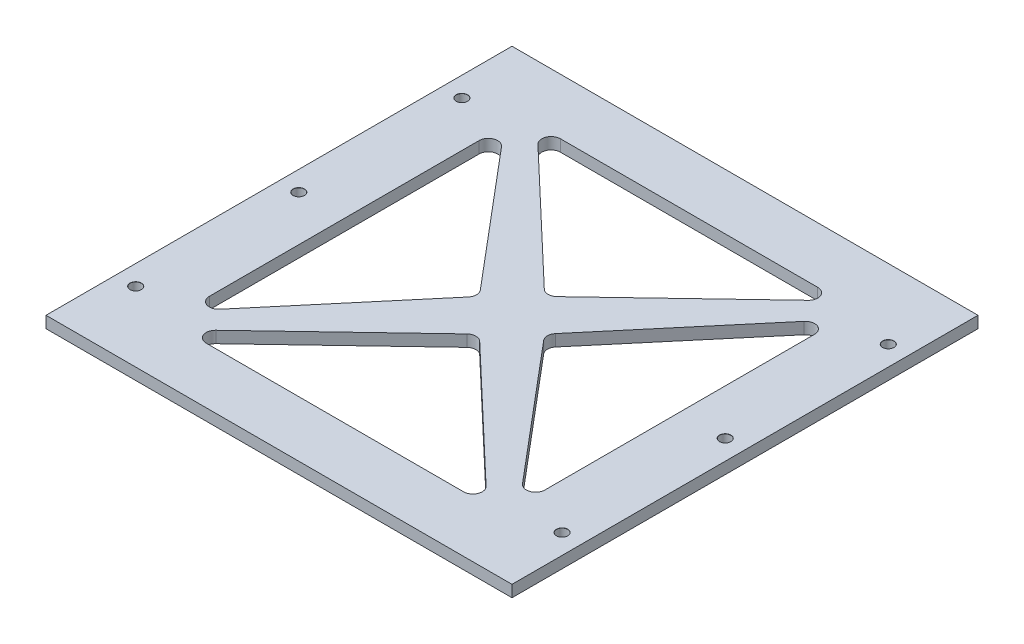
SolidWorks part; units mm, degrees
material "6061-T6 (SS)"
ref_plane "Front Plane" through (0, 0, 0) normal (0, 0, 1) x (1, 0, 0)
ref_plane "Top Plane" through (0, 0, 0) normal (0, 1, 0) x (1, 0, 0)
ref_plane "Right Plane" through (0, 0, 0) normal (1, 0, 0) x (0, 0, -1)
sketch "Sketch2" plane through (0, 0, 0) normal (0, 1, 0) x (1, 0, 0)
  line L1 (-50, -50) -> (50, -50)
  line L2 (-50, -50) -> (-50, 50)
  line L3 (-50, 50) -> (50, 50)
  line L4 (50, -50) -> (50, 50)
  line L5 (-50, -50) -> (50, 50) construction
  line L6 (-50, 50) -> (50, -50) construction
  point P0 (0, 0)
  dimension "D1" = 100
  dimension "D2" = 100
extrude "Boss-Extrude1" add sketch "Sketch2" along normal blind 2.5
hole_wizard "M2 Clearance Hole1" positions "Sketch3" profile "Sketch4" hole size "M2" standard "ANSI Metric" end condition up to next
sketch "Sketch3" plane through (0, 2.5, 0) normal (0, 1, 0) x (1, 0, 0)
  line L0 (-50, 50) -> (-50, -50) construction
  line L1 (50, 50) -> (-50, 50) construction
  point P0 (-45.75, 35)
  dimension "D1" = 4.25
  dimension "D2" = 15
sketch "Sketch4" plane through (-45.75, 2.5, -35) normal (1, 0, 0) x (0, 0, 1)
  line L0 (0, 0) -> (0, 2.5)
  line L1 (0, 2.5) -> (1.2, 2.5)
  line L2 (1.2, 2.5) -> (1.2, 0.025)
  line L3 (1.2, 0.025) -> (1.225, 0)
  line L5 (1.225, 0) -> (0, 0)
  line L6 (-1.2, 0.025) -> (-1.225, 0) construction
  line L11 (0, -6.35) -> (0, 107.95) construction
  dimension "Thru Hole Dia." = 2.4
  dimension "Thru Hole Depth" = 2.5
  dimension "Near C'Sink Dia." = 2.45
  dimension "Near C'Sink Angle" = 90
pattern_linear "LPattern1" count 3 spacing 35 along (0, 0, 1) of "M2 Clearance Hole1"
mirror "Mirror1" about plane through (0, 0, 0) normal (1, 0, 0) of "LPattern1", "M2 Clearance Hole1"
sketch "Sketch5" plane through (0, 2.5, 0) normal (0, 1, 0) x (1, 0, 0)
  line L0 (1.3778, 8.3094) -> (28.9891, 34.5503)
  line L1 (27.6113, 38) -> (-27.6113, 38)
  line L2 (-28.9891, 34.5503) -> (-1.3778, 8.3094)
  line L3 (50, 50) -> (-50, 50) construction
  line L4 (0, 53.7704) -> (0, -54.1757) construction
  line L5 (-61.6738, 0) -> (81.1285, 0) construction
  line L6 (27.6113, -38) -> (-27.6113, -38)
  line L7 (1.3778, -8.3094) -> (28.9891, -34.5503)
  line L8 (-28.9891, -34.5503) -> (-1.3778, -8.3094)
  line L9 (-36, 28.9328) -> (-36, -28.9328)
  line L10 (-32.4707, -30.2217) -> (-8.0863, -1.2889)
  line L11 (-8.0863, 1.2889) -> (-32.4707, 30.2217)
  line L12 (-50, 50) -> (-50, -50) construction
  line L13 (32.4707, -30.2217) -> (8.0863, -1.2889)
  line L14 (36, 28.9328) -> (36, -28.9328)
  line L15 (8.0863, 1.2889) -> (32.4707, 30.2217)
  arc A0 (28.9891, 34.5503) -> (27.6113, 38) centre (27.6113, 36) ccw
  arc A1 (1.3778, 8.3094) -> (-1.3778, 8.3094) centre (0, 9.7591) cw
  arc A2 (-27.6113, 38) -> (-28.9891, 34.5503) centre (-27.6113, 36) ccw
  arc A3 (-27.6113, -38) -> (-28.9891, -34.5503) centre (-27.6113, -36) cw
  arc A4 (27.6113, -38) -> (28.9891, -34.5503) centre (27.6113, -36) ccw
  arc A5 (1.3778, -8.3094) -> (-1.3778, -8.3094) centre (0, -9.7591) ccw
  arc A6 (-36, -28.9328) -> (-32.4707, -30.2217) centre (-34, -28.9328) ccw
  arc A7 (-8.0863, -1.2889) -> (-8.0863, 1.2889) centre (-9.6156, 0) ccw
  arc A8 (-36, 28.9328) -> (-32.4707, 30.2217) centre (-34, 28.9328) cw
  arc A9 (36, -28.9328) -> (32.4707, -30.2217) centre (34, -28.9328) cw
  arc A10 (8.0863, -1.2889) -> (8.0863, 1.2889) centre (9.6156, 0) cw
  arc A11 (36, 28.9328) -> (32.4707, 30.2217) centre (34, 28.9328) ccw
  point P6 (0, 38)
  point P16 (32.619, 38)
  point P19 (0, 7)
  point P22 (-32.619, 38)
  point P25 (-32.619, -38)
  point P28 (32.619, -38)
  point P31 (0, -7)
  point P34 (-36, 0)
  point P42 (-7, 0)
  point P45 (-36, 34.4093)
  dimension "D4" = 2
  dimension "D5" = 2
  dimension "D9" = 2
  dimension "D1" = 12
  dimension "D2" = 7
  dimension "D3" = 45
  dimension "D6" = 45
  dimension "D7" = 14
  dimension "D8" = 7
extrude "Cut-Extrude1" cut sketch "Sketch5" against normal blind 2.5 contours L11 A8 L9 A6 L10 A7 | L2 A1 L0 A0 L1 A2 | L13 A10 L15 A11 L14 A9 | L6 A3 L8 A5 L7 A4
